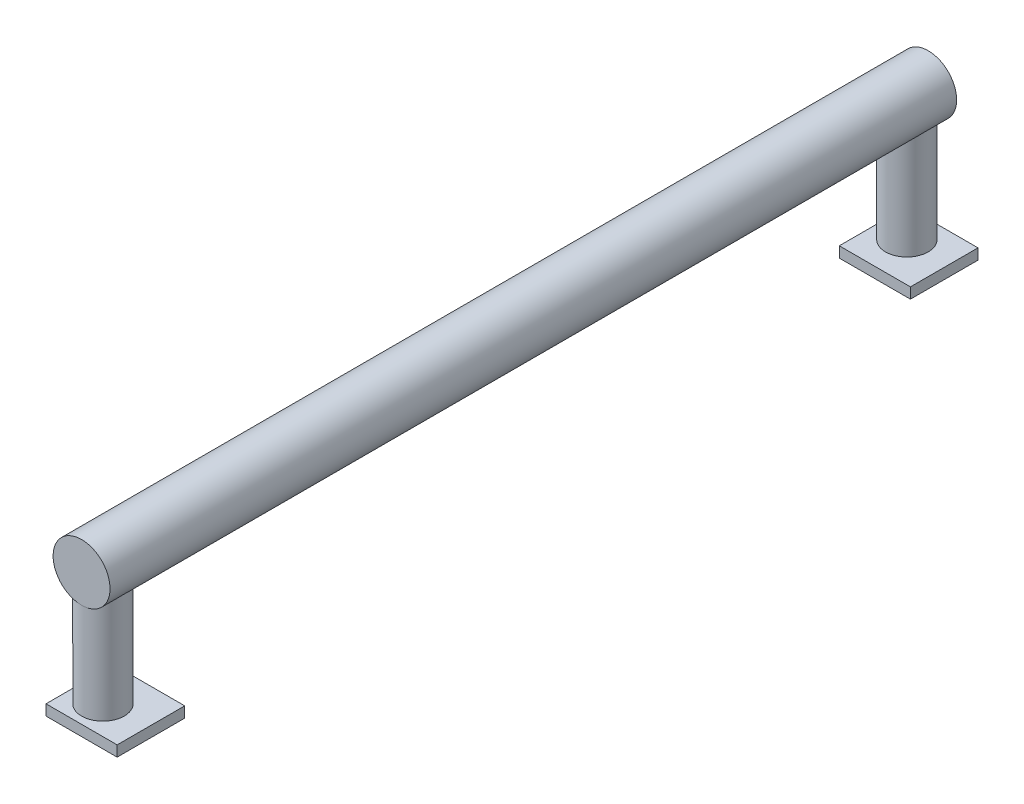
SolidWorks part; units mm, degrees
ref_plane "Front Plane" through (0, 0, 0) normal (0, 0, 1) x (1, 0, 0)
ref_plane "Top Plane" through (0, 0, 0) normal (0, 1, 0) x (1, 0, 0)
ref_plane "Right Plane" through (0, 0, 0) normal (1, 0, 0) x (0, 0, -1)
sketch "SK_P01_Foot" plane through (0, 0, 0) normal (0, 1, 0) x (1, 0, 0)
  line L0 (-10, -121) -> (10, -121)
  line L1 (10, -121) -> (10, -102)
  line L2 (10, -102) -> (-10, -102)
  line L3 (-10, -102) -> (-10, -121)
extrude "P01_Foot" add sketch "SK_P01_Foot" along normal blind 3
sketch "SK_P02_Foot" plane through (0, 0, 0) normal (0, 1, 0) x (1, 0, 0)
  line L0 (-10, 102) -> (10, 102)
  line L1 (10, 102) -> (10, 121)
  line L2 (10, 121) -> (-10, 121)
  line L3 (-10, 121) -> (-10, 102)
extrude "P02_Foot" add sketch "SK_P02_Foot" along normal blind 3
sketch "SK_P03_Leg" plane through (0, 0, 0) normal (0, 1, 0) x (1, 0, 0)
  circle A0 centre (-2, -113) radius 6
extrude "P03_Leg" add sketch "SK_P03_Leg" along normal blind 35 from offset 3
sketch "SK_P04_Leg" plane through (0, 0, 0) normal (0, 1, 0) x (1, 0, 0)
  circle A0 centre (-2, 113) radius 6
extrude "P04_Leg" add sketch "SK_P04_Leg" along normal blind 35 from offset 3
sketch "SK_P05_Grip" plane through (0, 0, 0) normal (0, 0, 1) x (1, 0, 0)
  circle A0 centre (-2, 38) radius 8
extrude "P05_Grip" add sketch "SK_P05_Grip" along normal blind 238 from offset 119
